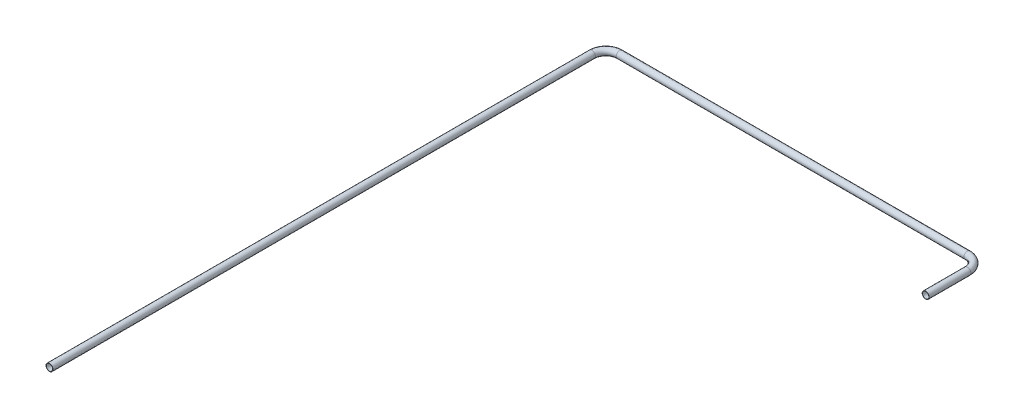
SolidWorks part; units mm, degrees
ref_plane "Front" through (0, 0, 0) normal (0, 0, 1) x (1, 0, 0)
ref_plane "Top" through (0, 0, 0) normal (0, 1, 0) x (1, 0, 0)
ref_plane "Right" through (0, 0, 0) normal (1, 0, 0) x (0, 0, -1)
sketch "Sketch13" plane through (0, 0, 0) normal (0, 1, 0) x (1, 0, 0)
  line L0 (-152.4, 0) -> (-3962.4, 0)
  line L1 (-4114.8, -152.4) -> (-4114.8, -6096)
  line L2 (0, -152.4) -> (0, -609.6)
  arc A0 (-4114.8, -152.4) -> (-3962.4, 0) centre (-3962.4, -152.4) cw
  arc A1 (0, -152.4) -> (-152.4, 0) centre (-152.4, -152.4) ccw
  point P7 (-4114.8, 0)
  point P10 (0, 0)
  dimension "D3" = 152.4
  dimension "D1" = 6096
  dimension "D2" = 609.6
  dimension "D4" = 3810
ref_plane "Plane1" through (0, 0, 609.6) normal (0, 0, 1) x (1, 0, 0)
sketch "Sketch14" plane through (0, 0, 609.6) normal (0, 0, 1) x (1, 0, 0)
  line L0 (0, 34.925) -> (0, 38.1) construction
  circle A0 centre (0, 0) radius 38.1
  circle A1 centre (0, 0) radius 34.925
  dimension "D1" = 76.2
  dimension "D2" = 3.175
sweep "Sweep1" add profiles "Sketch14" path "Sketch13"
